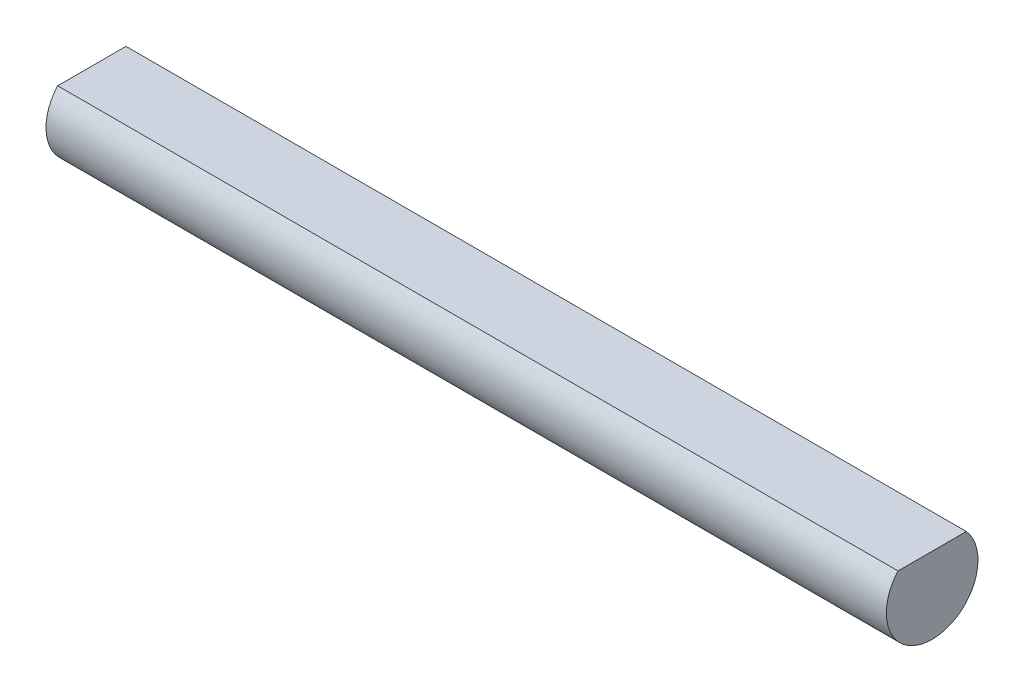
SolidWorks part; units mm, degrees
ref_plane "Front Plane" through (0, 0, 0) normal (0, 0, 1) x (1, 0, 0)
ref_plane "Top Plane" through (0, 0, 0) normal (0, 1, 0) x (1, 0, 0)
ref_plane "Right Plane" through (0, 0, 0) normal (1, 0, 0) x (0, 0, -1)
sketch "Sketch1" plane through (0, 0, 0) normal (1, 0, 0) x (0, 0, -1)
  line L0 (-2.2361, 2) -> (2.2361, 2)
  arc A0 (-2.2361, 2) -> (2.2361, 2) centre (0, 0) ccw
  arc A1 (2.2361, 2) -> (-2.2361, 2) centre (0, 0) ccw construction
  point P5 (0, -3)
  dimension "D1" = 6
  dimension "D2" = 5
extrude "Boss-Extrude1" add sketch "Sketch1" along normal mid plane 55 contours A0 L0
